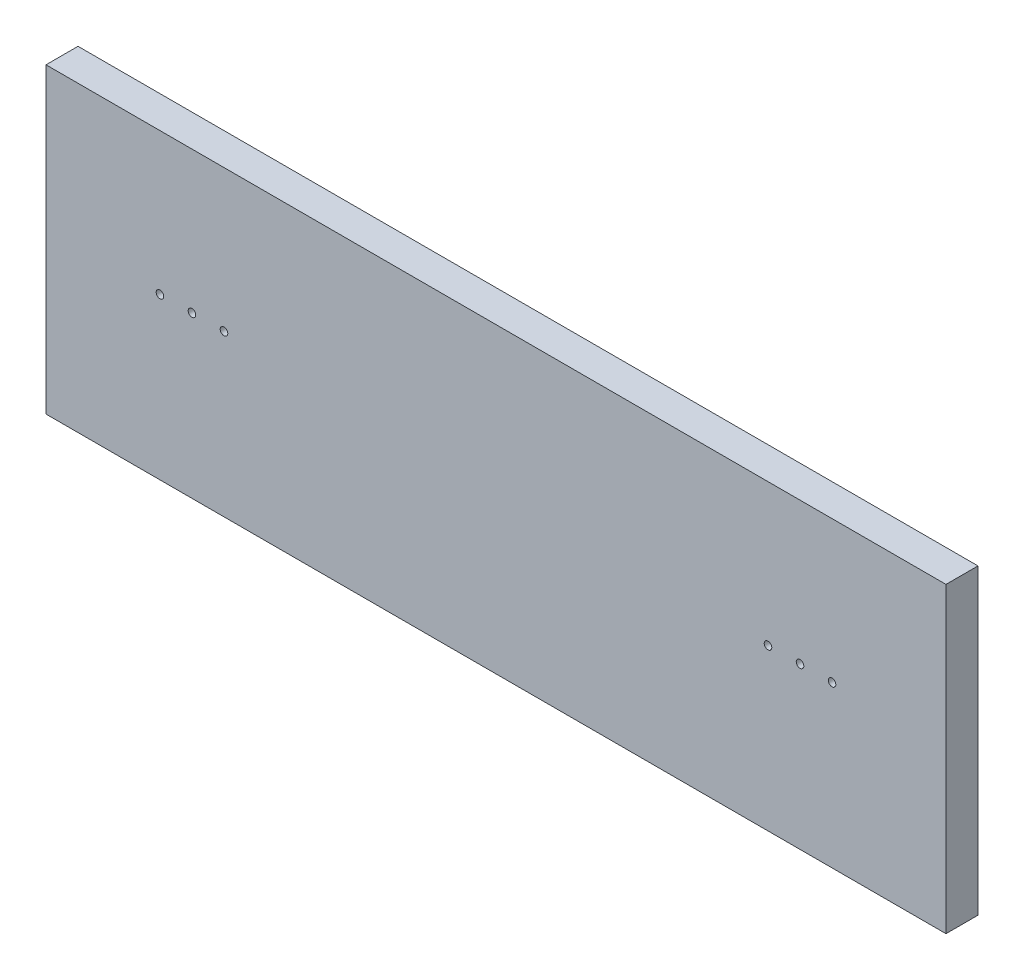
SolidWorks part; units mm, degrees
ref_plane "前视基准面" through (0, 0, 0) normal (0, 0, 1) x (1, 0, 0)
ref_plane "上视基准面" through (0, 0, 0) normal (0, 1, 0) x (1, 0, 0)
ref_plane "右视基准面" through (0, 0, 0) normal (1, 0, 0) x (0, 0, -1)
sketch "草图1" plane through (0, 0, 0) normal (0, 0, 1) x (1, 0, 0)
  line L1 (-178.5, 60) -> (178.5, 60)
  line L2 (-178.5, 60) -> (-178.5, -60)
  line L3 (-178.5, -60) -> (178.5, -60)
  line L4 (178.5, 60) -> (178.5, -60)
  line L5 (-178.5, 60) -> (178.5, -60) construction
  line L6 (-178.5, -60) -> (178.5, 60) construction
  point P0 (0, 0)
  dimension "D1" = 120
  dimension "D2" = 357
extrude "凸台-拉伸1" add sketch "草图1" along normal blind 12.7
sketch "草图2" plane through (0, 0, 12.7) normal (0, 0, 1) x (1, 0, 0)
  line L0 (178.5, -60) -> (178.5, 60) construction
  line L1 (178.5, 60) -> (-178.5, 60) construction
  line L2 (0, 60) -> (0, -60) construction
  line L3 (-178.5, -60) -> (178.5, -60) construction
  circle A4 centre (133.3, 3.72) radius 1.5
  circle A6 centre (120.6, 3.72) radius 1.5
  circle A7 centre (107.9, 3.72) radius 1.5
  circle A8 centre (-107.9, 3.72) radius 1.5
  circle A9 centre (-120.6, 3.72) radius 1.5
  circle A10 centre (-133.3, 3.72) radius 1.5
  dimension "D2" = 56.28
  dimension "D3" = 3
  dimension "D1" = 45.2
  dimension "D5" = 12.7
  dimension "D4" = 3
extrude "切除-拉伸1" cut sketch "草图2" against normal through all
